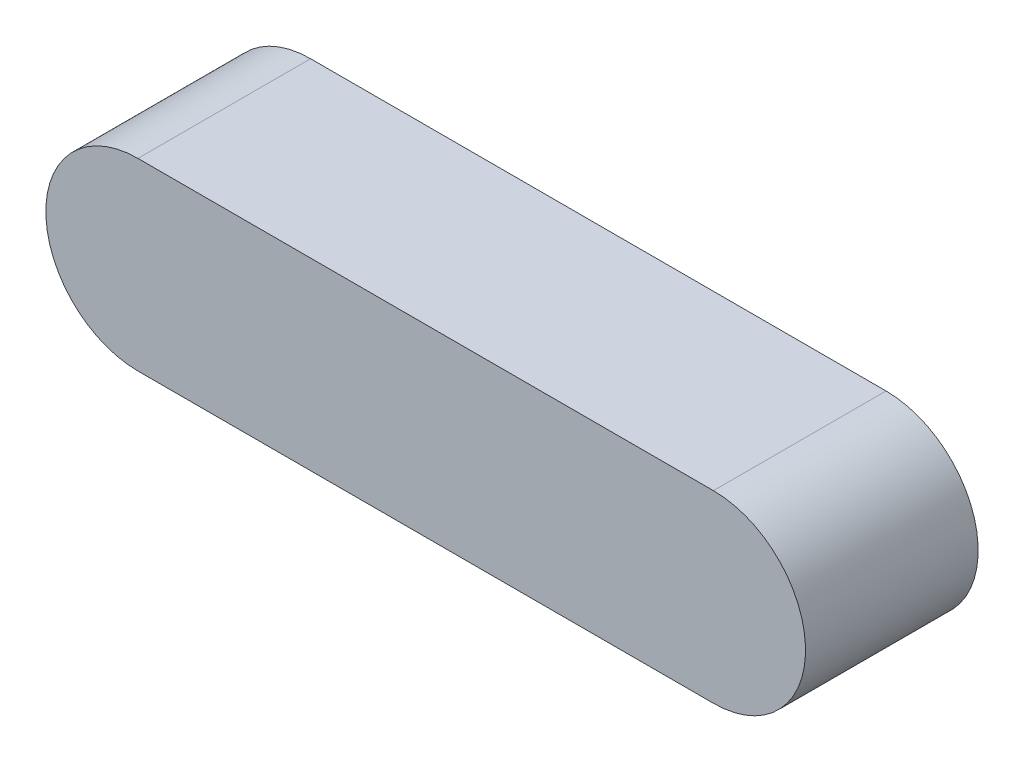
SolidWorks part; units mm, degrees
ref_plane "Front Plane" through (0, 0, 0) normal (0, 0, 1) x (1, 0, 0)
ref_plane "Top Plane" through (0, 0, 0) normal (0, 1, 0) x (1, 0, 0)
ref_plane "Right Plane" through (0, 0, 0) normal (1, 0, 0) x (0, 0, -1)
sketch "Sketch1" plane through (0, 0, 0) normal (0, 0, 1) x (1, 0, 0)
  line L0 (-12.5, 0) -> (12.5, 0) construction
  line L1 (-12.5, 4) -> (12.5, 4)
  line L2 (-12.5, -4) -> (12.5, -4)
  arc A0 (-12.5, 4) -> (-12.5, -4) centre (-12.5, 0) ccw
  arc A1 (12.5, -4) -> (12.5, 4) centre (12.5, 0) ccw
  point P2 (0, 0)
  dimension "D1" = 4
  dimension "D2" = 25
extrude "Boss-Extrude1" add sketch "Sketch1" along normal blind 7.5
